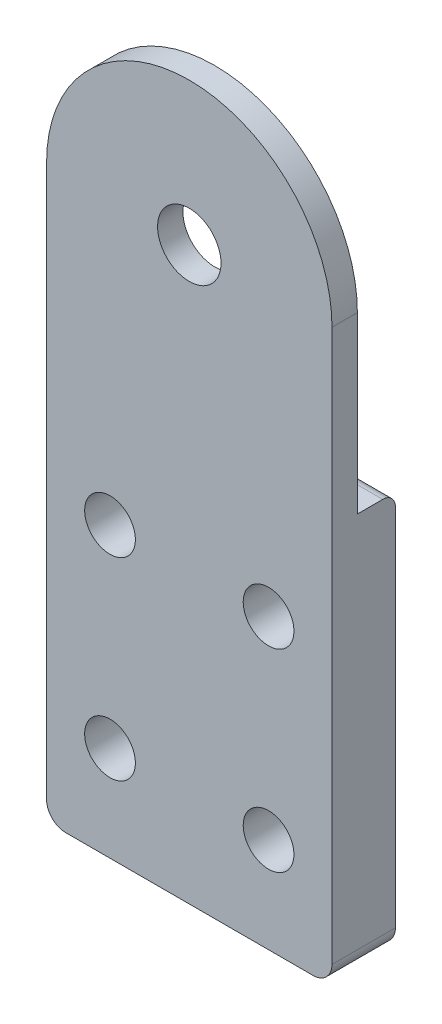
SolidWorks part; units mm, degrees
ref_plane "前视基准面" through (0, 0, 0) normal (0, 0, 1) x (1, 0, 0)
ref_plane "上视基准面" through (0, 0, 0) normal (0, 1, 0) x (1, 0, 0)
ref_plane "右视基准面" through (0, 0, 0) normal (1, 0, 0) x (0, 0, -1)
other "Configuration Table"
sketch "草图1" plane through (0, 0, 0) normal (0, 0, 1) x (1, 0, 0)
  line L0 (-22.5, 0) -> (-22.5, -87)
  line L6 (-19.5, -90) -> (19.5, -90)
  line L7 (-22.5, -90) -> (-22.5, 0)
  line L8 (-22.5, 0) -> (22.5, 0) construction
  line L9 (22.5, -87) -> (22.5, 0)
  arc A0 (22.5, 0) -> (-22.5, 0) centre (0, 0) ccw
  arc A1 (-22.5, 0) -> (22.5, 0) centre (0, 0) ccw construction
  arc A2 (19.5, -90) -> (22.5, -87) centre (19.5, -87) ccw
  arc A3 (-22.5, -87) -> (-19.5, -90) centre (-19.5, -87) ccw
  point P0 (0, 0)
  dimension "D1" = 45
  dimension "D3" = 3
  dimension "D2" = 90
extrude "凸台-拉伸1" add sketch "草图1" along normal blind 10 contours L0 A3 L6 A2 L9 A0
sketch "草图2" plane through (0, 0, 0) normal (0, 0, -1) x (-1, 0, 0)
  line L1 (22.5, 0) -> (22.5, -87) construction
  line L4 (-22.5, -27.5) -> (22.5, -27.5)
  line L6 (-22.5, -27.5) -> (22.5, -27.5)
  line L7 (-22.5, -27.5) -> (-22.5, 22.5)
  line L8 (-22.5, 22.5) -> (22.5, 22.5)
  line L9 (22.5, -27.5) -> (22.5, 22.5)
  line M10 (22.5, -87) -> (22.5, 0)
  arc M11 (22.5, 0) -> (-22.5, 0) centre (0, 0) ccw
  line M12 (-22.5, 0) -> (-22.5, -87)
  dimension "D1" = 27.5
  dimension "D2" = 22.5
  dimension "D4" = 45
  dimension "D5" = 50
extrude "切除-拉伸1" cut sketch "草图2" against normal blind 6 contours L4 M12 M10 M11
fillet "圆角1" radius 2 1 edges at (0, -27.5, 0)
sketch "草图3" plane through (0, 0, 10) normal (0, 0, 1) x (1, 0, 0)
  circle A0 centre (0, 0) radius 5
  dimension "D1" = 10
extrude "切除-拉伸2" cut sketch "草图3" against normal blind 6
sketch "草图5" plane through (0, 0, 0) normal (0, 0, -1) x (-1, 0, 0)
  line L0 (-22.5, -90) -> (-22.5, -75) construction
  line L1 (12.5, -90) -> (22.5, -90) construction
  line L2 (-22.5, -75) -> (-22.5, -44.5) construction
  line L3 (-22.5, -29.5) -> (-12.5, -29.5) construction
  line L4 (22.5, -44.5) -> (22.5, -29.5) construction
  line L5 (-22.5, -29.5) -> (-12.5, -29.5) construction
  line L6 (-22.5, -29.5) -> (-22.5, -44.5) construction
  line L7 (-16.5, -44.5) -> (-12.5, -44.5) construction
  line L8 (-12.5, -40.5) -> (-12.5, -44.5) construction
  line L9 (-22.5, -90) -> (-12.5, -90) construction
  line L10 (-22.5, -90) -> (-22.5, -75) construction
  line L11 (-16.5, -75) -> (-12.5, -75) construction
  line L12 (-12.5, -79) -> (-12.5, -75) construction
  line L13 (22.5, -90) -> (12.5, -90) construction
  line L14 (22.5, -90) -> (22.5, -75)
  line L15 (16.5, -75) -> (12.5, -75) construction
  line L16 (12.5, -79) -> (12.5, -75) construction
  line L17 (22.5, -29.5) -> (12.5, -29.5) construction
  line L18 (22.5, -29.5) -> (22.5, -44.5)
  line L19 (16.5, -44.5) -> (12.5, -44.5) construction
  line L20 (12.5, -29.5) -> (12.5, -40.5) construction
  line L21 (-12.5, -90) -> (-12.5, -79) construction
  line L22 (-22.5, -90) -> (-12.5, -90) construction
  line L23 (-12.5, -90) -> (12.5, -90) construction
  line L24 (-22.5, -75) -> (-16.5, -75) construction
  line L25 (22.5, -90) -> (22.5, -75) construction
  line L26 (12.5, -90) -> (12.5, -79) construction
  line L27 (22.5, -75) -> (16.5, -75) construction
  line L28 (22.5, -75) -> (22.5, -44.5) construction
  line L29 (22.5, -44.5) -> (16.5, -44.5) construction
  line L30 (12.5, -40.5) -> (12.5, -44.5) construction
  line L31 (12.5, -29.5) -> (22.5, -29.5) construction
  line L32 (-12.5, -29.5) -> (12.5, -29.5) construction
  line L33 (-12.5, -29.5) -> (-12.5, -40.5) construction
  line L34 (-22.5, -44.5) -> (-22.5, -29.5) construction
  line L35 (-22.5, -44.5) -> (-16.5, -44.5) construction
  circle A0 centre (-12.5, -44.5) radius 4
  circle A1 centre (-12.5, -75) radius 4
  circle A2 centre (12.5, -75) radius 4
  circle A3 centre (12.5, -44.5) radius 4
  dimension "D6" = 8
  dimension "D11" = 10
  dimension "D12" = 8
  dimension "D14" = 8
  dimension "D15" = 8
  dimension "D1" = 29.5
  dimension "D2" = 60.5
  dimension "D3" = 45
  dimension "D4" = 15
  dimension "D5" = 10
  dimension "D7" = 10
  dimension "D8" = 15
  dimension "D9" = 10
  dimension "D10" = 15
  dimension "D13" = 15
extrude "切除-拉伸3" cut sketch "草图5" against normal through all contours A0 | A3 | A2 | A1
